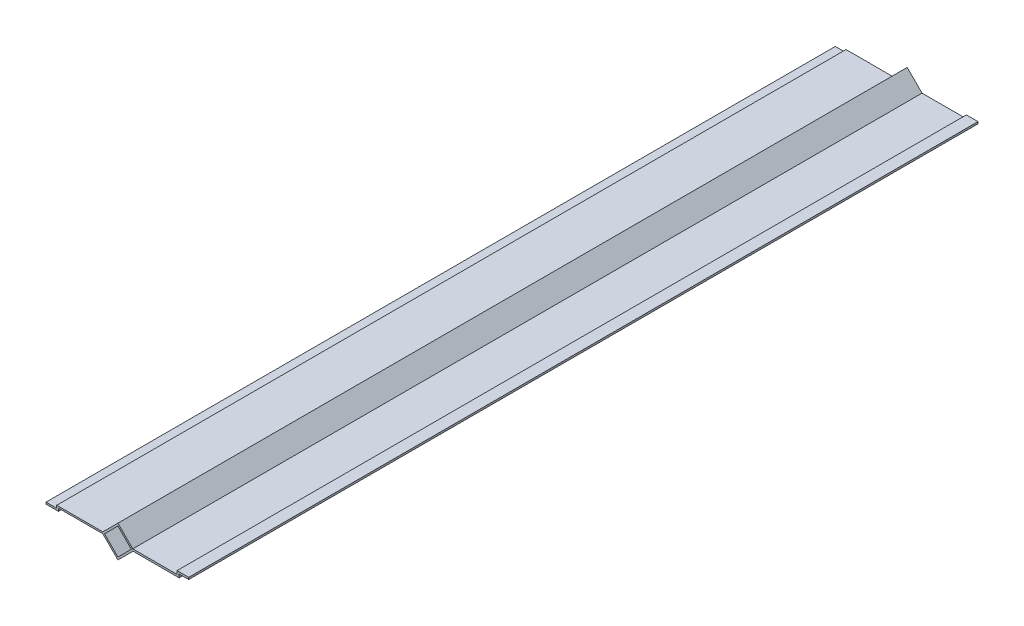
SolidWorks part; units mm, degrees
material "1060 Alloy"
ref_plane "Front Plane" through (0, 0, 0) normal (0, 0, 1) x (1, 0, 0)
ref_plane "Top Plane" through (0, 0, 0) normal (0, 1, 0) x (1, 0, 0)
ref_plane "Right Plane" through (0, 0, 0) normal (1, 0, 0) x (0, 0, -1)
sketch "Sketch1" plane through (0, 0, 0) normal (0, 0, 1) x (1, 0, 0)
  line L5 (-15, 0) -> (0, 15)
  line L6 (-66.3851, 0.9433) -> (-16.8851, 0.9433)
  line L18 (-66.3851, -0.9433) -> (-66.3851, -2.0433)
  line L19 (-66.3851, -0.9433) -> (-16.8851, -0.9433)
  line L20 (66.0908, 1.2377) -> (16.5908, 1.2377)
  line L21 (68.3851, -0.9433) -> (16.8851, -0.9433)
  line L23 (-80.3851, -2.0433) -> (-80.3851, -4.0433)
  line L24 (-68.3851, -2.0433) -> (-68.3851, 0.9433)
  line L25 (-68.3851, 0.9433) -> (-66.3851, 0.9433)
  line L26 (-68.3851, -2.0433) -> (-80.3851, -2.0433)
  line L27 (-68.3851, -4.0433) -> (-80.3851, -4.0433)
  line L28 (-66.3851, -2.0433) -> (-66.3851, -4.0433)
  line L29 (-66.3851, -4.0433) -> (-68.3851, -4.0433)
  line L30 (66.0908, 1.2377) -> (66.0908, 2.9377)
  line L32 (68.3851, 2.7567) -> (68.3851, -0.9433)
  line L34 (68.3851, 2.7567) -> (79.0908, 2.7567)
  line L35 (66.0908, 2.9377) -> (66.0908, 4.9377)
  line L36 (66.0908, 4.9377) -> (79.0908, 4.9377)
  line L37 (79.0908, 4.9377) -> (79.0908, 2.7567)
  line L38 (-16.8851, 0.9433) -> (0, 17.8284)
  line L39 (0, 17.8284) -> (16.5908, 1.2377)
  line L40 (16.8851, -0.9433) -> (0, -17.8284)
  line L41 (-16.8851, -0.9433) -> (0, -17.8284)
  line L42 (0, 15) -> (15, 0)
  line L43 (15, 0) -> (15, 0)
  line L44 (15, 0) -> (15, 0)
  line L45 (15, 0) -> (15, 0)
  line L46 (15, 0) -> (15, 0)
  line L47 (15, 0) -> (15, 0)
  line L48 (15, 0) -> (15, 0)
  line L49 (15, 0) -> (15, 0)
  line L50 (15, 0) -> (15, 0)
  line L51 (15, 0) -> (0, -15)
  line L52 (-15, 0) -> (0, -15)
  line L53 (-15, 0) -> (-15, 0)
  line L54 (-15, 0) -> (-15, 0)
  line L55 (-15, 0) -> (-15, 0)
  line L56 (-15, 0) -> (-15, 0)
  line L57 (-15, 0) -> (-15, 0)
  line L58 (-15, 0) -> (-15, 0)
  line L59 (-15, 0) -> (-15, 0)
  line L60 (-15, 0) -> (-15, 0)
  line L61 (-15, 0) -> (-15, 0)
  line L62 (-15, 0) -> (-15, 0)
  point P5 (-24.0416, 0)
  point P6 (0, 24.0416)
  point P7 (24.0416, 0)
  point P8 (0, -24.0416)
  point P10 (0, 0)
  point P20 (0, 0)
  dimension "D1" = 2
  dimension "D2" = 30
  dimension "D3" = 51.5
  dimension "D4" = 49.5
  dimension "D5" = 2
  dimension "D6" = 2
  dimension "D7" = 51.5
  dimension "D8" = 49.5
  dimension "D9" = 13
  dimension "D10" = 30
extrude "Boss-Extrude1" add sketch "Sketch1" along normal blind 882
